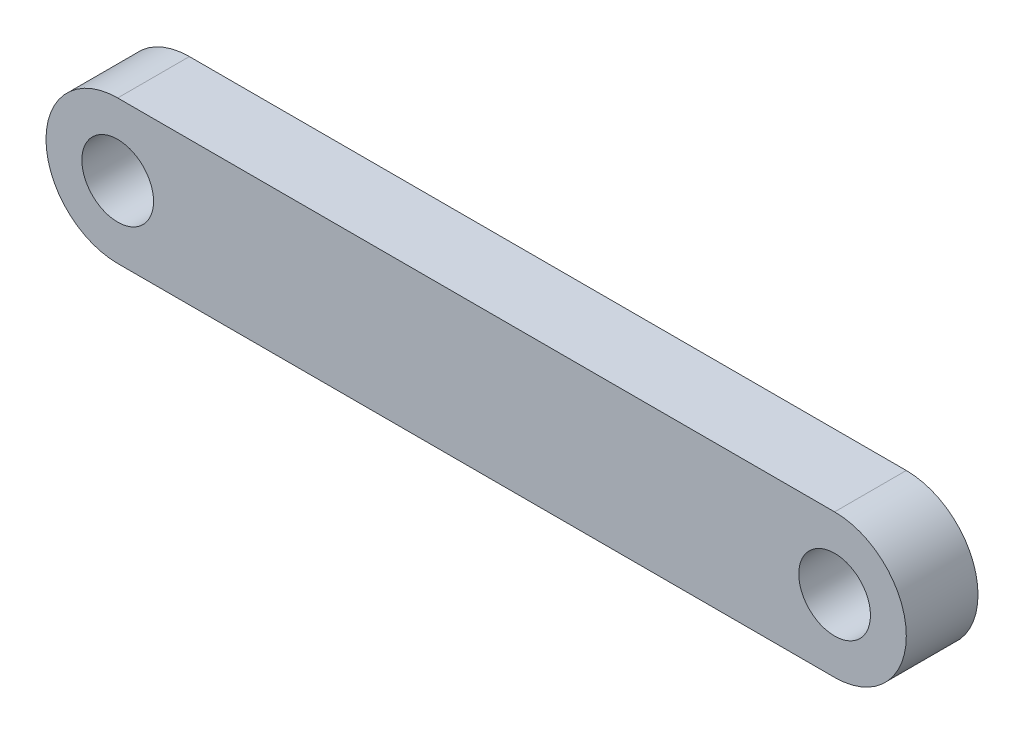
SolidWorks part; units mm, degrees
ref_plane "Front Plane" through (0, 0, 0) normal (0, 0, 1) x (1, 0, 0)
ref_plane "Top Plane" through (0, 0, 0) normal (0, 1, 0) x (1, 0, 0)
ref_plane "Right Plane" through (0, 0, 0) normal (1, 0, 0) x (0, 0, -1)
sketch "Sketch1" plane through (0, 0, 0) normal (0, 0, 1) x (1, 0, 0)
  line L0 (0, 0) -> (100, 0) construction
  line L1 (0, 10) -> (100, 10)
  line L2 (0, -10) -> (100, -10)
  arc A0 (0, 10) -> (0, -10) centre (0, 0) ccw
  arc A1 (100, -10) -> (100, 10) centre (100, 0) ccw
  circle A2 centre (0, 0) radius 5
  circle A3 centre (100, 0) radius 5
  point P3 (50, 0)
  dimension "D3" = 10
  dimension "D4" = 10
  dimension "D1" = 20
  dimension "D2" = 100
extrude "Boss-Extrude1" add sketch "Sketch1" along normal blind 10
